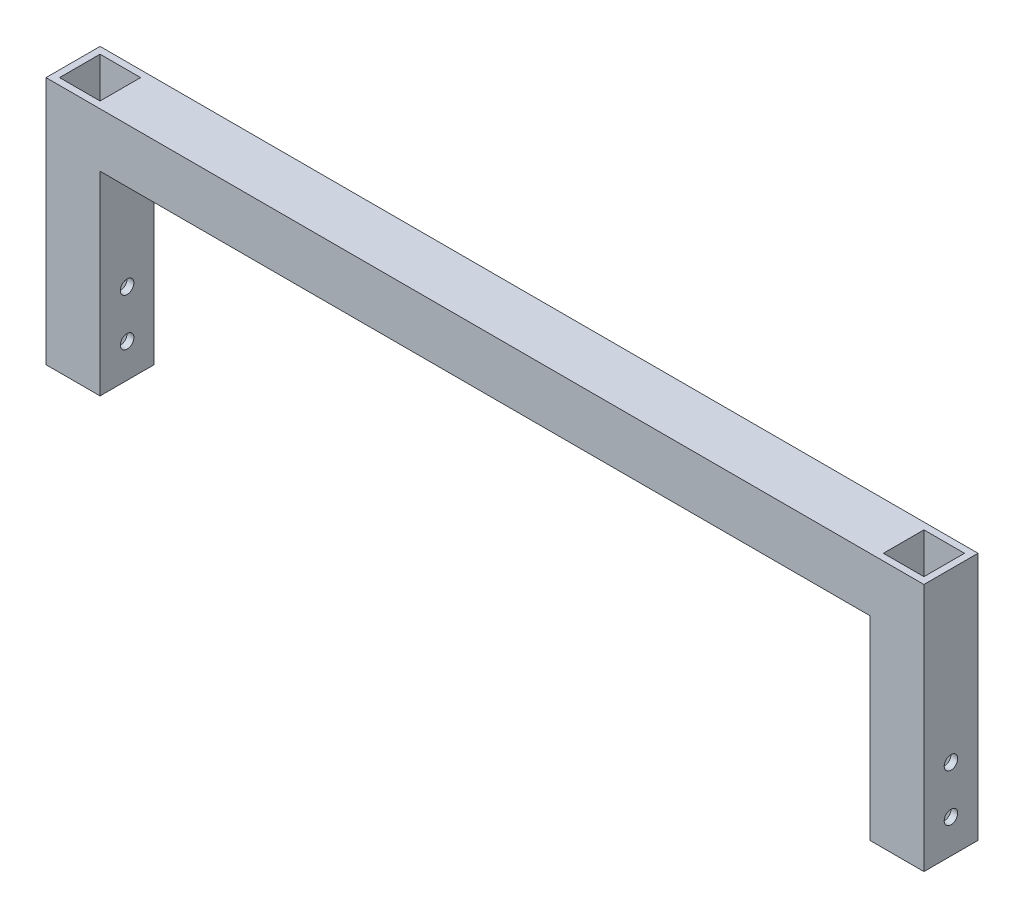
SolidWorks part; units mm, degrees
ref_plane "FRONT" through (0, 0, 0) normal (0, 0, 1) x (1, 0, 0)
ref_plane "TOP" through (0, 0, 0) normal (0, 1, 0) x (1, 0, 0)
ref_plane "RIGHT" through (0, 0, 0) normal (1, 0, 0) x (0, 0, -1)
sketch "Sketch1" plane through (0, 0, 0) normal (0, 1, 0) x (1, 0, 0)
  line L1 (0, 0) -> (19.05, 0)
  line L2 (0, 0) -> (0, 19.05)
  line L3 (0, 19.05) -> (19.05, 19.05)
  line L4 (19.05, 0) -> (19.05, 19.05)
  line L5 (-3.175, -3.175) -> (22.225, -3.175)
  line L6 (-3.175, -3.175) -> (-3.175, 22.225)
  line L7 (-3.175, 22.225) -> (22.225, 22.225)
  line L8 (22.225, -3.175) -> (22.225, 22.225)
  dimension "D1" = 3.175
  dimension "D2" = 3.175
  dimension "D3" = 3.175
  dimension "D4" = 3.175
  dimension "D5" = 25.4
  dimension "D6" = 25.4
extrude "Boss-Extrude1" add sketch "Sketch1" along normal blind 116.84
sketch "Sketch2" plane through (-3.175, 0, 0) normal (-1, 0, 0) x (0, 0, 1)
  line L0 (-22.225, 0) -> (3.175, 0) construction
  line L1 (3.175, 116.84) -> (3.175, 0) construction
  circle A0 centre (-9.525, 15.875) radius 3.175
  circle A1 centre (-9.525, 38.1) radius 3.175
  dimension "D3" = 6.35
  dimension "D4" = 6.35
  dimension "D1" = 15.875
  dimension "D2" = 12.7
  dimension "D5" = 12.7
  dimension "D6" = 22.225
extrude "Cut-Extrude1" cut sketch "Sketch2" against normal blind 25.4
sketch "Sketch4" plane through (22.225, 0, 0) normal (1, 0, 0) x (0, 0, -1)
  line L0 (22.225, 116.84) -> (22.225, 0) construction
  line L1 (-3.175, 116.84) -> (22.225, 116.84)
  line L2 (-3.175, 116.84) -> (-3.175, 91.44)
  line L3 (-3.175, 91.44) -> (22.225, 91.44)
  line L4 (22.225, 116.84) -> (22.225, 91.44)
  line L6 (19.05, 94.615) -> (0, 94.615)
  line L7 (19.05, 94.615) -> (19.05, 113.665)
  line L8 (19.05, 113.665) -> (0, 113.665)
  line L9 (0, 94.615) -> (0, 113.665)
  dimension "D1" = 25.4
  dimension "D2" = 3.175
  dimension "D3" = 3.175
  dimension "D4" = 3.175
  dimension "D5" = 3.175
extrude "Boss-Extrude2" add sketch "Sketch4" along normal blind 180.848
ref_plane "Plane1" through (203.073, 0, 0) normal (1, 0, 0) x (0, 0, -1)
mirror "Mirror2" about plane through (203.073, 0, 0) normal (1, 0, 0) of "Boss-Extrude2", "Boss-Extrude1"
mirror "Mirror4" about plane through (203.073, 0, 0) normal (1, 0, 0) of "Cut-Extrude1", "Boss-Extrude1"
